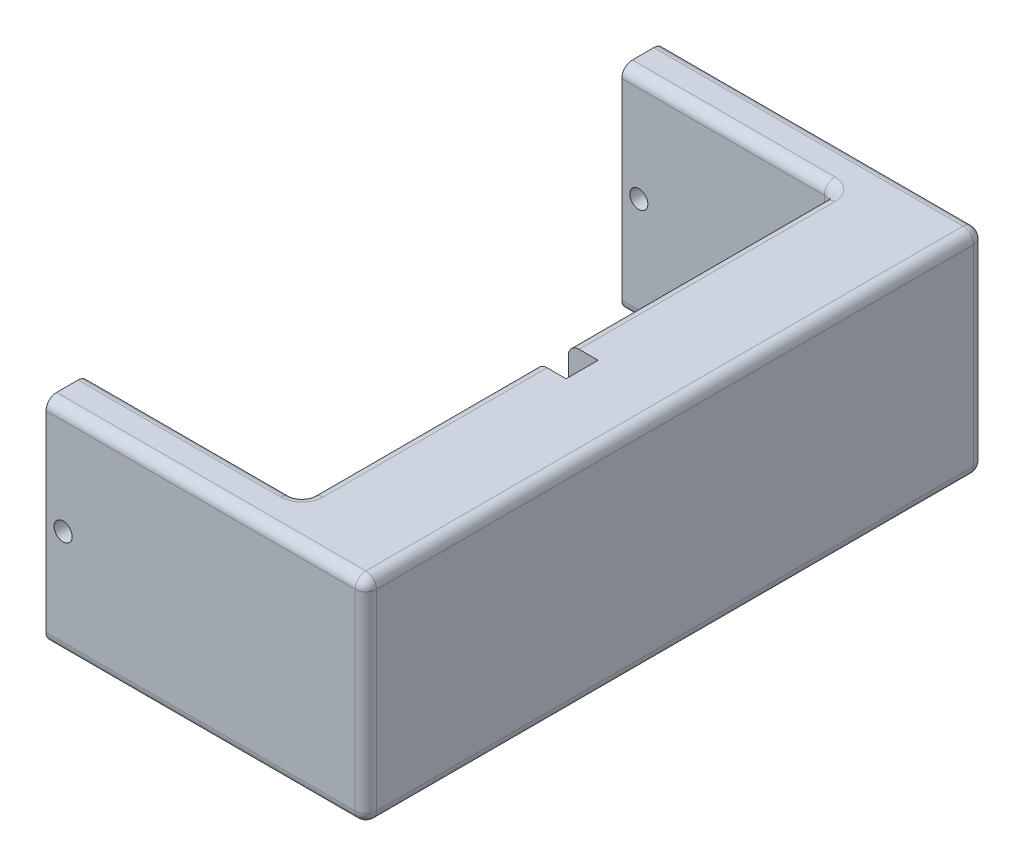
SolidWorks part; units mm, degrees
ref_plane "Alzado" through (0, 0, 0) normal (0, 0, 1) x (1, 0, 0)
ref_plane "Planta" through (0, 0, 0) normal (0, 1, 0) x (1, 0, 0)
ref_plane "Vista lateral" through (0, 0, 0) normal (1, 0, 0) x (0, 0, -1)
sketch "Croquis1" plane through (0, 0, 0) normal (0, 1, 0) x (1, 0, 0)
  line L0 (0, -1.45) -> (1.5, -1.45)
  line L1 (1.5, -1.45) -> (1.5, 1.45)
  line L2 (1.5, 1.45) -> (0, 1.45)
  line L3 (0, 1.45) -> (0, 1.25)
  line L4 (0, 1.25) -> (1, 1.25)
  line L5 (1, 1.25) -> (1, -1.25)
  line L6 (1, -1.25) -> (0, -1.25)
  line L7 (0, -1.25) -> (0, -1.45)
  dimension "D1" = 0.2
  dimension "D2" = 0.2
  dimension "D3" = 1.5
  dimension "D4" = 0.5
  dimension "D5" = 1.5
  dimension "D6" = 2.5
  dimension "D7" = 1.25
extrude "Saliente-Extruir1" add sketch "Croquis1" along normal blind 1
fillet "Redondeo1" radius 0.05 16 edges at (1, 0, 0) (0.5, 1, 1.25) (1, 1, 0) (0.75, 1, -1.45) (0.75, 1, 1.45) (0.75, 0, 1.45) (1.5, 0.5, 1.45) (1.5, 1, 0) (1.5, 0.5, -1.45) (1.5, 0, 0) (0.5, 1, -1.25) (1, 0.5, -1.25) (0.5, 0, -1.25) (1, 0.5, 1.25) (0.5, 0, 1.25) (0.75, 0, -1.45)
sketch "Croquis2" plane through (0, 0, 1.45) normal (0, 0, 1) x (1, 0, 0)
  line L1 (0, 1) -> (1.45, 1) construction
  line L2 (0, 0.95) -> (0, 0.05) construction
  circle A0 centre (0.08, 0.5) radius 0.0423
  dimension "D1" = 0.08
  dimension "D2" = 0.5
extrude "Cortar-Extruir1" cut sketch "Croquis2" against normal through all
sketch "Croquis3" plane through (0, 1, 0) normal (0, 1, 0) x (1, 0, 0)
  line L1 (0.9085, -0.0003) -> (1.1392, -0.0003)
  line L4 (0.9085, -0.1503) -> (1.1392, -0.1503)
  line L6 (0.9085, -0.1503) -> (0.9085, -0.0003)
  line L7 (1.1392, -0.0003) -> (1.1392, -0.1503)
  dimension "D2" = 0.15
extrude "Cortar-Extruir2" cut sketch "Croquis3" against normal blind 0.2
